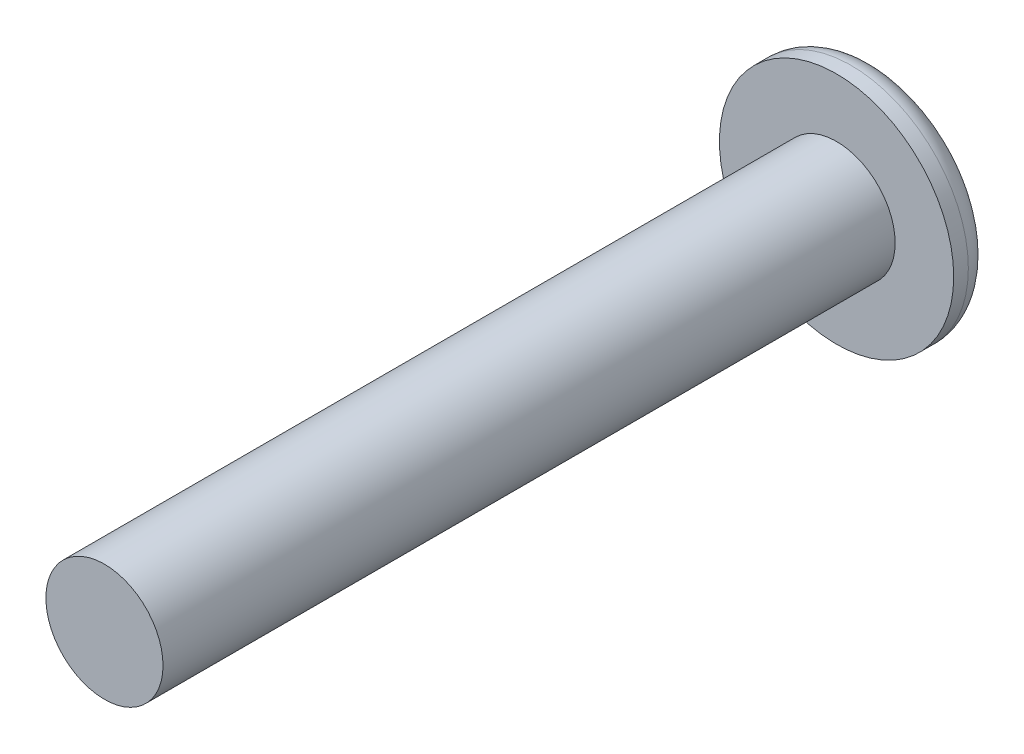
SolidWorks part; units mm, degrees
ref_plane "前视基准面" through (0, 0, 0) normal (0, 0, 1) x (1, 0, 0)
ref_plane "上视基准面" through (0, 0, 0) normal (0, 1, 0) x (1, 0, 0)
ref_plane "右视基准面" through (0, 0, 0) normal (1, 0, 0) x (0, 0, -1)
sketch "草图1" plane through (0, 0, 0) normal (0, 0, 1) x (1, 0, 0)
  circle A0 centre (0, 0) radius 4
  dimension "D1" = 8
extrude "凸台-拉伸1" add sketch "草图1" along normal blind 1.3
sketch "草图2" plane through (0, 0, 1.3) normal (0, 0, 1) x (1, 0, 0)
  circle A0 centre (0, 0) radius 2
  dimension "D1" = 4
extrude "凸台-拉伸2" add sketch "草图2" along normal blind 25
sketch "草图3" plane through (0, 0, 0) normal (0, 0, -1) x (-1, 0, 0)
  line L1 (-0.7217, 1.25) -> (-1.4434, 0)
  line L2 (-1.4434, 0) -> (-0.7217, -1.25)
  line L3 (-0.7217, -1.25) -> (0.7217, -1.25)
  line L4 (0.7217, -1.25) -> (1.4434, 0)
  line L5 (1.4434, 0) -> (0.7217, 1.25)
  line L6 (0.7217, 1.25) -> (-0.7217, 1.25)
  circle A0 centre (0, 0) radius 1.25 construction
  dimension "D1" = 2.5
extrude "切除-拉伸1" cut sketch "草图3" against normal blind 1.2
fillet "圆角1" radius 0.8 1 edges at (4, 0, 0)
